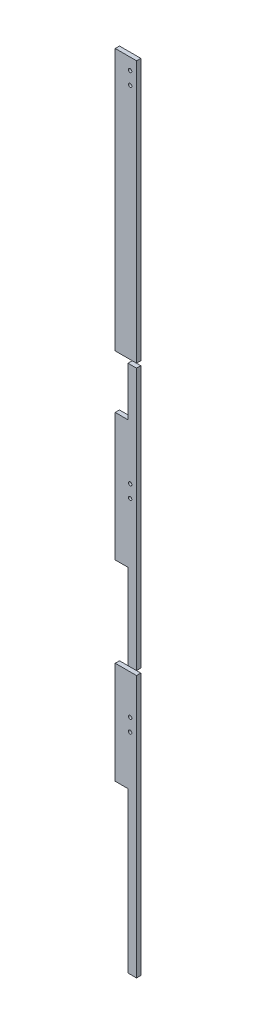
SolidWorks part; units mm, degrees
material "轻木"
ref_plane "前视基准面" through (0, 0, 0) normal (0, 0, 1) x (1, 0, 0)
ref_plane "上视基准面" through (0, 0, 0) normal (0, 1, 0) x (1, 0, 0)
ref_plane "右视基准面" through (0, 0, 0) normal (1, 0, 0) x (0, 0, -1)
other "Configuration Table"
sketch "草图1" plane through (0, 0, 0) normal (0, 0, 1) x (1, 0, 0)
  line L1 (120.7876, -767.01) -> (130.7876, -767.01)
  line L2 (120.7876, -767.01) -> (120.7876, -890.01)
  line L3 (120.7876, -890.01) -> (130.7876, -890.01)
  line L4 (130.7876, -767.01) -> (130.7876, -890.01)
  line L6 (126.7876, -771.51) -> (142.7876, -771.51) construction
  line L7 (120.7876, -975.01) -> (126.7876, -975.01)
  line L8 (120.7876, -975.01) -> (120.7876, -915.01)
  line L9 (120.7876, -915.01) -> (126.7876, -915.01)
  line L10 (130.7876, -985.01) -> (130.7876, -925.01)
  line L11 (120.7876, -892.01) -> (120.7876, -1015.01) construction
  line L12 (130.7876, -1015.01) -> (-45.1255, -1015.01) construction
  line L13 (130.7876, -1140.01) -> (-45.1255, -1140.01) construction
  line L14 (120.7876, -1017.01) -> (130.7876, -1017.01)
  line L15 (120.7876, -1017.01) -> (120.7876, -1065.01)
  line L16 (120.7876, -1065.01) -> (126.7876, -1065.01)
  line L17 (130.7876, -1017.01) -> (130.7876, -1076.01)
  line L19 (130.7876, -1076.01) -> (130.7876, -1140.01)
  line L20 (130.7876, -1140.01) -> (126.7876, -1140.01)
  line L21 (126.7876, -1065.01) -> (126.7876, -1140.01)
  line L22 (127.7876, -772.51) -> (127.7876, -778.51) construction
  line L24 (130.7876, -985.01) -> (130.7876, -1015.01)
  line L25 (130.7876, -1015.01) -> (126.7876, -1015.01)
  line L26 (126.7876, -975.01) -> (126.7876, -1015.01)
  line L27 (130.7876, -892.01) -> (126.7876, -892.01)
  line L28 (130.7876, -892.01) -> (130.7876, -925.01)
  line L30 (126.7876, -892.01) -> (126.7876, -915.01)
  line L31 (127.7876, -772.51) -> (127.7876, -940.51) construction
  line L32 (127.7876, -940.51) -> (127.7876, -1035.51) construction
  circle A0 centre (127.7876, -772.51) radius 0.8
  circle A1 centre (127.7876, -778.51) radius 0.8
  circle A2 centre (127.7876, -940.51) radius 0.8
  circle A3 centre (127.7876, -946.51) radius 0.8
  circle A4 centre (127.7876, -1035.51) radius 0.8
  circle A5 centre (127.7876, -1041.51) radius 0.8
  dimension "D4" = 7
  dimension "D9" = 1
  dimension "D10" = 1.6
  dimension "D1" = 60
  dimension "D2" = 40
  dimension "D3" = 4
  dimension "D5" = 48
  dimension "D6" = 10
  dimension "D7" = 4
  dimension "D8" = 4
  dimension "D11" = 6
  dimension "D13" = 168
  dimension "D15" = 95
  dimension "D12" = 2
  dimension "D14" = 2
extrude "凸台-拉伸1" add sketch "草图1" along normal blind 2
